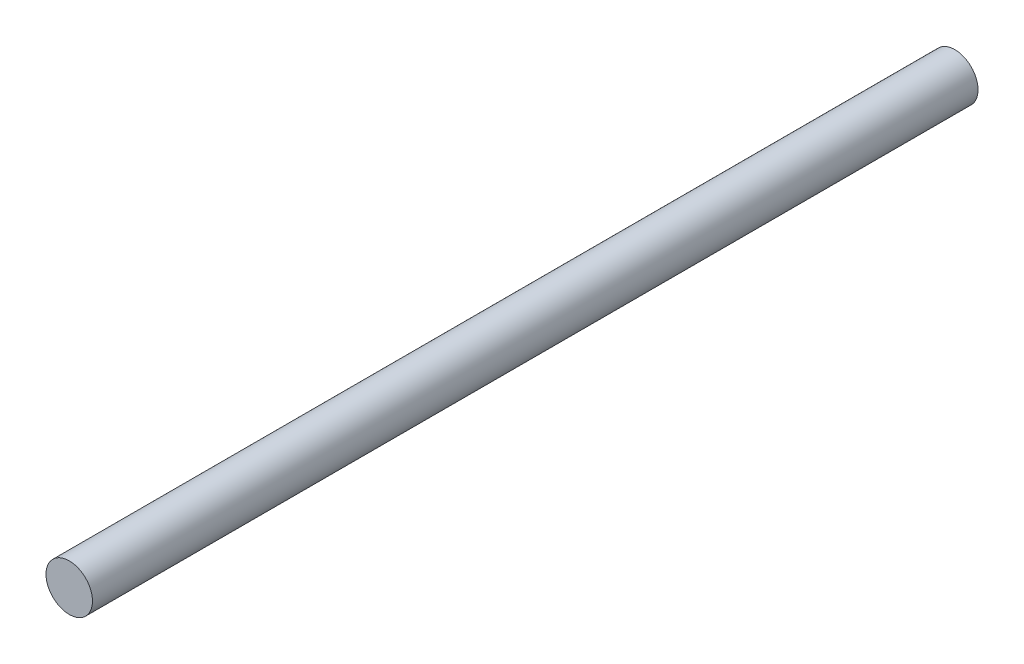
SolidWorks part; units mm, degrees
ref_plane "Front Plane" through (0, 0, 0) normal (0, 0, 1) x (1, 0, 0)
ref_plane "Top Plane" through (0, 0, 0) normal (0, 1, 0) x (1, 0, 0)
ref_plane "Right Plane" through (0, 0, 0) normal (1, 0, 0) x (0, 0, -1)
sketch "Sketch3" plane through (0, 0, 0) normal (0, 0, 1) x (1, 0, 0)
  circle A0 centre (0, 0) radius 4
  dimension "D1" = 8
extrude "Boss-Extrude1" add sketch "Sketch3" along normal blind 152.4
